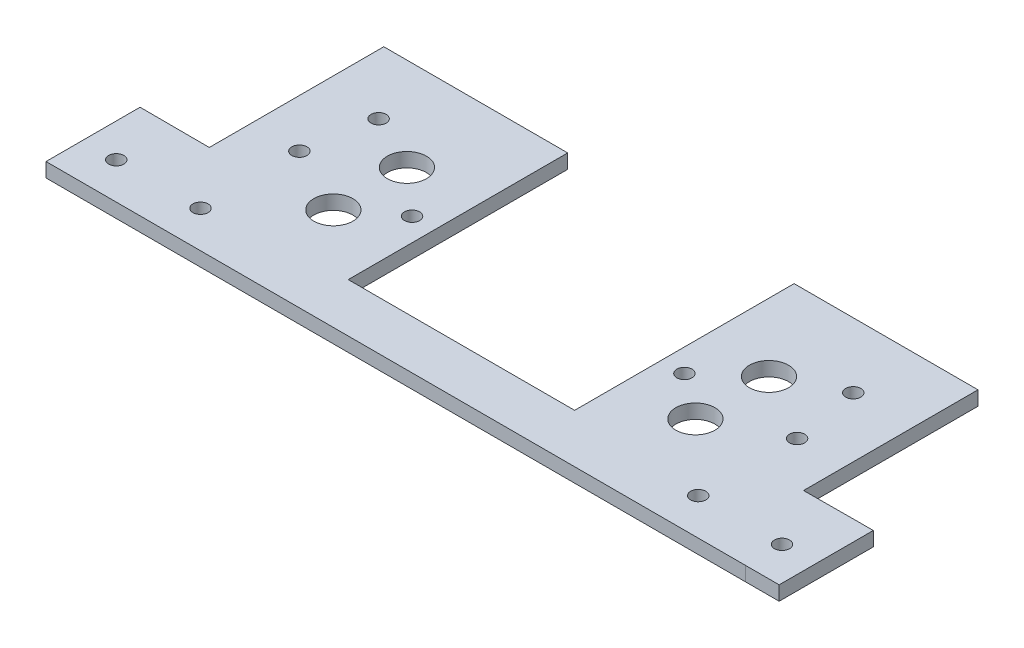
SolidWorks part; units mm, degrees
material "Copper"
ref_plane "Front Plane" through (0, 0, 0) normal (0, 0, 1) x (1, 0, 0)
ref_plane "Top Plane" through (0, 0, 0) normal (0, 1, 0) x (1, 0, 0)
ref_plane "Right Plane" through (0, 0, 0) normal (1, 0, 0) x (0, 0, -1)
sketch "Sketch1" plane through (0, 0, 0) normal (0, 1, 0) x (1, 0, 0)
  line L0 (44.3513, -40.0144) -> (37.1363, -40.0144)
  line L1 (0, 0) -> (0, -46.6159) construction
  line L2 (-19.6486, -28.7674) -> (44.3513, -28.7674) construction
  line L3 (-36.4337, -40.0144) -> (-36.4337, -46.6159)
  line L4 (37.1363, -40.0144) -> (37.1363, -46.6159)
  line L5 (-36.4337, -40.0144) -> (-43.6487, -40.0144)
  line L6 (-32.4727, -10.3704) -> (-32.4727, -29.6479)
  line L7 (-32.4727, 38.1938) -> (-32.4727, -29.6479) construction
  line L8 (-19.6486, -20.6394) -> (46.7444, -20.6394) construction
  line L9 (-42.3787, -29.6159) -> (-32.4727, -29.6479)
  line L10 (-12.1556, -10.3704) -> (-32.4727, -10.3704)
  line L11 (29.9683, -46.6159) -> (37.1363, -46.6159)
  line L12 (44.3513, -40.0144) -> (44.3513, -31.6519)
  line L13 (42.3513, -29.6159) -> (38.7463, -29.6159)
  line L14 (38.7463, -29.6159) -> (33.1753, -29.6479)
  line L15 (-11.5577, -34.6159) -> (-12.1556, -34.6159)
  line L16 (-12.1556, -34.6159) -> (-12.1556, -10.3704)
  line L17 (33.1753, -29.6479) -> (33.1753, 37.3661) construction
  line L18 (33.1753, -12.9294) -> (33.1753, -29.6479)
  line L19 (12.8581, -10.3704) -> (33.1753, -10.3704)
  line L20 (33.1753, -10.3704) -> (33.1753, -12.9294)
  line L21 (-43.6487, -29.6479) -> (-43.6487, -44.6339) construction
  line L22 (-43.6487, -30.8859) -> (-43.6487, -40.0144)
  line L23 (-36.4337, -46.6159) -> (-30.0837, -46.6159)
  line L24 (-30.0837, -46.6159) -> (29.9683, -46.6159)
  line L25 (-11.5577, -34.6159) -> (12.2603, -34.6159)
  line L28 (-43.6487, -30.8859) -> (-43.6487, -29.6479)
  line L29 (-43.6487, -29.6479) -> (-42.3787, -29.6159)
  line L30 (44.3513, -31.6519) -> (44.3513, -29.6479)
  line L31 (44.3513, -29.6479) -> (42.3513, -29.6159)
  line L32 (12.2603, -34.6159) -> (12.8581, -34.6159)
  line L33 (12.8581, -34.6159) -> (12.8581, -10.3704)
  circle A0 centre (-36.4337, -35.9659) radius 0.8382
  circle A1 centre (37.1363, -35.9839) radius 0.8382
  circle A2 centre (-19.6486, -28.7674) radius 2.159
  circle A3 centre (-19.6486, -20.6394) radius 2.159
  circle A4 centre (20.3514, -20.6394) radius 2.159
  circle A5 centre (20.3514, -28.7674) radius 2.159
  circle A6 centre (-25.8687, -17.5479) radius 0.8382
  circle A7 centre (26.5713, -17.5479) radius 0.8382
  dimension "D2" = 1.6764
  dimension "D5" = 1.6764
  dimension "D8" = 4.318
  dimension "D3" = 4.318
  dimension "D6" = 4.318
  dimension "D9" = 4.318
  dimension "D10" = 8.128
  dimension "D1" = 12
  dimension "D4" = 0
  dimension "D7" = 0
  dimension "D11" = 8.128
  dimension "D12" = 0
extrude "Boss-Extrude1" add sketch "Sketch1" along normal blind 1.575
sketch "Sketch2" plane through (0, 0, 0) normal (0, -1, 0) x (1, 0, 0)
  line L2 (-49.1064, 40.0139) -> (37.1363, 40.0139)
  line L4 (-49.1064, 40.0139) -> (-49.1064, 46.6159)
  line L6 (-49.1064, 46.6159) -> (37.1363, 46.6159)
  line L7 (37.1363, 40.0139) -> (37.1363, 46.6159)
  line L10 (-49.1064, 40.0139) -> (37.1363, 46.6159) construction
  line L12 (-49.1064, 46.6159) -> (37.1363, 40.0139) construction
  point P0 (-5.985, 43.3149)
  dimension "D1" = 6.602
extrude "Cut-Extrude1" cut sketch "Sketch2" against normal through all
sketch "Sketch3" plane through (0, 0, 0) normal (0, -1, 0) x (1, 0, 0)
  line L0 (-40.1487, 40.0139) -> (-40.1487, 29.6232)
  line L1 (-43.6487, 40.0139) -> (37.1363, 40.0139) construction
  line L3 (-32.4727, 29.6479) -> (-42.3787, 29.6159) construction
  line L4 (-40.1487, 29.6232) -> (-34.7737, 29.6405)
  line L8 (-40.1487, 40.0139) -> (-46.7728, 40.0139)
  line L9 (-46.7728, 40.0139) -> (-46.7728, 8.9756)
  line L10 (-46.7728, 8.9756) -> (-34.7737, 8.9756)
  line L11 (-34.7737, 29.6405) -> (-34.7737, 8.9756)
extrude "Cut-Extrude2" cut sketch "Sketch3" against normal through all
sketch "Sketch4" plane through (0, 0, 0) normal (0, -1, 0) x (1, 0, 0)
  line L0 (40.8513, 40.0144) -> (40.8513, 32.4201)
  line L1 (35.4763, 29.6159) -> (35.4763, 10.3704)
  line L2 (35.4763, 10.3704) -> (54.7109, 10.3704)
  line L7 (54.7109, 10.3704) -> (54.7109, 40.0144)
  line L8 (37.1363, 40.0144) -> (44.3513, 40.0144) construction
  line L11 (44.3513, 40.0144) -> (44.3513, 29.6479) construction
  line L12 (40.8513, 32.4201) -> (40.8513, 29.6159)
  line L13 (42.3513, 29.6159) -> (38.7463, 29.6159) construction
  line L14 (40.8513, 29.6159) -> (35.4763, 29.6159)
  line L15 (40.8513, 40.0144) -> (54.7109, 40.0144)
  dimension "D2" = 3.5
extrude "Cut-Extrude3" cut sketch "Sketch4" against normal through all
sketch "Sketch6" plane through (0, 0, 0) normal (0, -1, 0) x (-1, 0, 0)
  circle A0 centre (27.1416, -35.9479) radius 0.8382
  circle A1 centre (27.1416, -25.0259) radius 0.8382
  circle A2 centre (14.6956, -25.0259) radius 0.8382
  circle A3 centre (-15.3981, -25.0259) radius 0.8382
  circle A4 centre (-27.8444, -25.0259) radius 0.8382
  circle A5 centre (-27.8444, -35.9479) radius 0.8382
extrude "Cut-Extrude4" cut sketch "Sketch6" against normal blind 2.54
